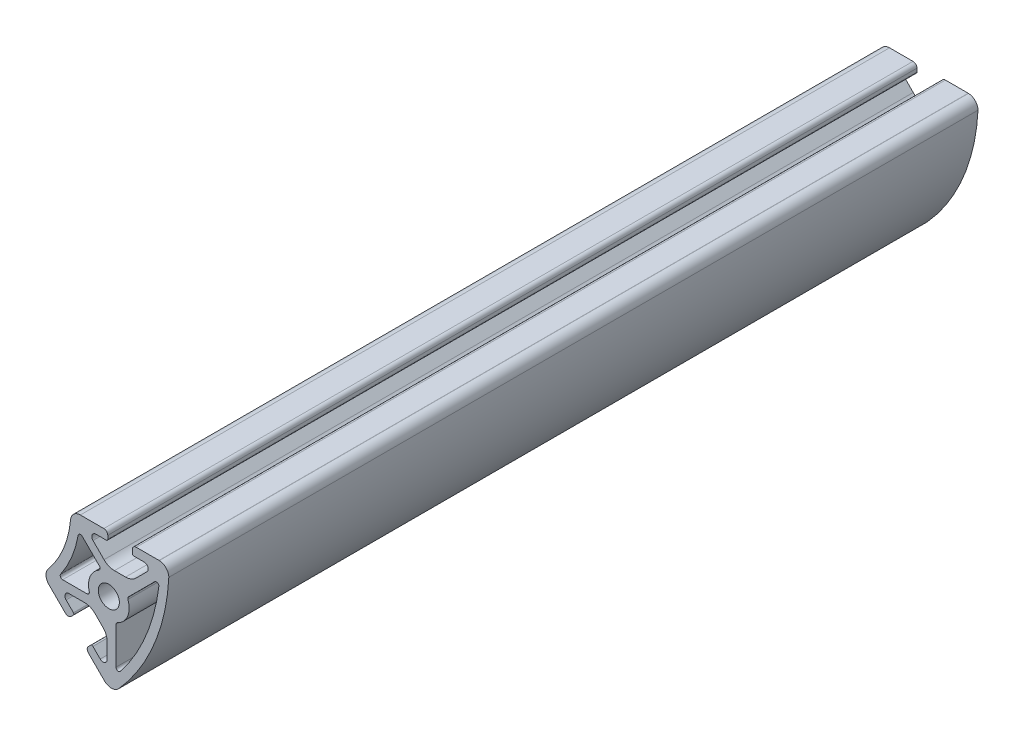
SolidWorks part; units mm, degrees
ref_plane "Front Plane" through (0, 0, 0) normal (0, 0, 1) x (1, 0, 0)
ref_plane "Top Plane" through (0, 0, 0) normal (0, 1, 0) x (1, 0, 0)
ref_plane "Right Plane" through (0, 0, 0) normal (1, 0, 0) x (0, 0, -1)
sketch "Sketch1" plane through (0, 0, 0) normal (0, 0, 1) x (1, 0, 0)
  line L0 (-12.1437, 13.1178) -> (-15.6366, 16.6108)
  line L1 (-19.64, 6.9458) -> (-14.7002, 6.9458)
  line L2 (-0.8709, 15.9853) -> (-6.2076, 10.6486)
  line L3 (-8.7567, 4.4944) -> (-8.7567, -3.0528)
  line L4 (-17.9338, 1.3105) -> (-17.4389, 1.8054)
  line L5 (-17.4389, 2.2297) -> (-18.9362, 3.7271)
  line L6 (-18.3476, 5.1481) -> (-15.1652, 5.1481)
  line L7 (-13.0439, 4.2694) -> (-11.4394, 2.6649)
  line L8 (-10.5607, 0.5436) -> (-10.5607, -2.6388)
  line L9 (-11.9817, -3.2274) -> (-13.4791, -1.7301)
  line L10 (-13.9033, -1.7301) -> (-14.3983, -2.2251)
  line L11 (-14.3983, -3.3564) -> (-11.0914, -6.6633)
  line L12 (-11.0914, -6.6633) -> (-11.0217, -6.7266)
  line L13 (0.0056, 20.187) -> (-4.6418, 20.187)
  line L14 (-5.4418, 19.387) -> (-5.4418, 18.687)
  line L15 (-5.1418, 18.387) -> (-3.0242, 18.387)
  line L16 (-2.4356, 16.966) -> (-4.6859, 14.7157)
  line L17 (-6.8072, 13.837) -> (-9.0763, 13.837)
  line L18 (-11.1977, 14.7157) -> (-13.448, 16.966)
  line L19 (-12.8594, 18.387) -> (-10.7418, 18.387)
  line L20 (-10.4418, 18.687) -> (-10.4418, 19.387)
  line L21 (-11.2418, 20.187) -> (-16.0329, 20.187)
  line L22 (-22.5571, 4.8111) -> (-22.4177, 4.6629)
  line L23 (-22.4177, 4.6629) -> (-19.0652, 1.3105)
  arc A0 (-20.0503, 7.7315) -> (-19.64, 6.9458) centre (-19.64, 7.4458) ccw
  arc A1 (-20.0503, 7.7315) -> (-16.4823, 16.3453) centre (-37.941, 20.1879) ccw
  arc A2 (-15.6366, 16.6108) -> (-16.4823, 16.3453) centre (-15.9902, 16.2572) ccw
  arc A3 (-12.2528, 12.328) -> (-12.1437, 13.1178) centre (-12.4972, 12.7643) ccw
  arc A4 (-12.2528, 12.328) -> (-14.2189, 7.5815) centre (-10.2246, 8.7074) ccw
  arc A5 (-19.0652, 1.3105) -> (-17.9338, 1.3105) centre (-18.4995, 1.8762) ccw
  arc A6 (-17.4389, 1.8054) -> (-17.4389, 2.2297) centre (-17.651, 2.0176) ccw
  arc A7 (-18.3476, 5.1481) -> (-18.9362, 3.7271) centre (-18.3476, 4.3157) ccw
  arc A8 (-13.0439, 4.2694) -> (-15.1652, 5.1481) centre (-15.1652, 2.1481) ccw
  arc A9 (-10.5607, 0.5436) -> (-11.4394, 2.6649) centre (-13.5607, 0.5436) ccw
  arc A10 (-11.9817, -3.2274) -> (-10.5607, -2.6388) centre (-11.3931, -2.6388) ccw
  arc A11 (-13.4791, -1.7301) -> (-13.9033, -1.7301) centre (-13.6912, -1.9422) ccw
  arc A12 (-14.3983, -2.2251) -> (-14.3983, -3.3564) centre (-13.8326, -2.7907) ccw
  arc A13 (-11.0217, -6.7266) -> (-8.2822, -6.6515) centre (-9.6918, -5.2328) ccw
  arc A14 (-8.2822, -6.6515) -> (2.0085, 18.1922) centre (-37.9418, 20.187) ccw
  arc A15 (2.0085, 18.1922) -> (0.0664, 20.185) centre (0.0085, 18.1858) ccw
  arc A16 (0.0664, 20.185) -> (0.0056, 20.187) centre (-0.0147, 18.6782) ccw
  arc A17 (-4.6418, 20.187) -> (-5.4418, 19.387) centre (-4.6418, 19.387) ccw
  arc A18 (-5.4418, 18.687) -> (-5.1418, 18.387) centre (-5.1418, 18.687) ccw
  arc A19 (-2.4356, 16.966) -> (-3.0242, 18.387) centre (-3.0242, 17.5546) ccw
  arc A20 (-6.8072, 13.837) -> (-4.6859, 14.7157) centre (-6.8072, 16.837) ccw
  arc A21 (-11.1977, 14.7157) -> (-9.0763, 13.837) centre (-9.0763, 16.837) ccw
  arc A22 (-12.8594, 18.387) -> (-13.448, 16.966) centre (-12.8594, 17.5546) ccw
  arc A23 (-10.7418, 18.387) -> (-10.4418, 18.687) centre (-10.7418, 18.687) ccw
  arc A24 (-10.4418, 19.387) -> (-11.2418, 20.187) centre (-11.2418, 19.387) ccw
  arc A25 (-16.0329, 20.187) -> (-18.0246, 18.3688) centre (-16.0329, 18.187) ccw
  arc A26 (-22.5725, 7.3891) -> (-18.0246, 18.3688) centre (-37.9418, 20.187) ccw
  arc A27 (-22.5725, 7.3891) -> (-22.5571, 4.8111) centre (-21.0356, 6.1093) ccw
  arc A28 (-14.7002, 6.9458) -> (-14.2189, 7.5815) centre (-14.7002, 7.4458) ccw
  arc A29 (-12.3754, 8.7065) -> (-8.0754, 8.7065) centre (-10.2254, 8.7065) ccw
  arc A30 (-8.0754, 8.7065) -> (-12.3754, 8.7065) centre (-10.2254, 8.7065) ccw
  arc A31 (-8.4683, 4.9474) -> (-6.324, 10.1243) centre (-10.2246, 8.7074) ccw
  arc A32 (-6.2076, 10.6486) -> (-6.324, 10.1243) centre (-5.854, 10.295) ccw
  arc A33 (-0.021, 15.5713) -> (-0.8709, 15.9853) centre (-0.5173, 15.6317) ccw
  arc A34 (-7.863, -3.3611) -> (-0.021, 15.5713) centre (-37.941, 20.1879) ccw
  arc A35 (-8.7567, -3.0528) -> (-7.863, -3.3611) centre (-8.2567, -3.0528) ccw
  arc A36 (-8.4683, 4.9474) -> (-8.7567, 4.4944) centre (-8.2567, 4.4944) ccw
extrude "Boss-Extrude1" add sketch "Sketch1" along normal blind 165
